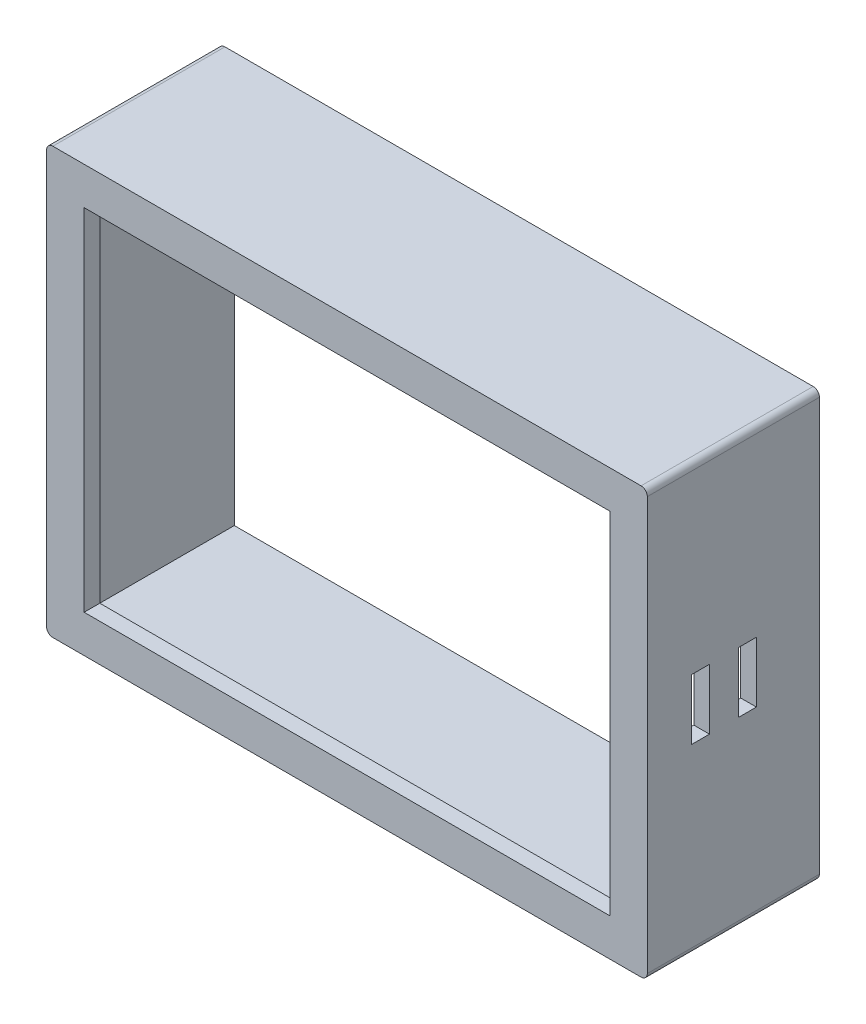
SolidWorks part; units mm, degrees
ref_plane "Front Plane" through (0, 0, 0) normal (0, 0, 1) x (1, 0, 0)
ref_plane "Top Plane" through (0, 0, 0) normal (0, 1, 0) x (1, 0, 0)
ref_plane "Right Plane" through (0, 0, 0) normal (1, 0, 0) x (0, 0, -1)
sketch "Sketch1" plane through (0, 0, 0) normal (0, 0, 1) x (1, 0, 0)
  line L0 (-48, 34) -> (48, 34)
  line L1 (-42, 28) -> (42, 28)
  line L2 (-42, 28) -> (-42, -28)
  line L3 (-42, -28) -> (42, -28)
  line L4 (42, 28) -> (42, -28)
  line L5 (-42, 28) -> (42, -28) construction
  line L6 (-42, -28) -> (42, 28) construction
  line L7 (48, 34) -> (48, -34)
  line L8 (-48, -34) -> (48, -34)
  line L9 (-48, 34) -> (-48, -34)
  point P0 (0, 0)
  dimension "D1" = 56
  dimension "D2" = 84
  dimension "D3" = 6
extrude "Boss-Extrude1" add sketch "Sketch1" against normal blind 2.5
sketch "Sketch2" plane through (0, 0, -2.5) normal (0, 0, -1) x (-1, 0, 0)
  line L4 (48, -34) -> (-48, -34) construction
  line L5 (48, 34) -> (48, -34) construction
  line L6 (-48, 34) -> (48, 34) construction
  line L7 (-48, -34) -> (-48, 34) construction
  line L8 (-45.5, -31.5) -> (45.5, -31.5)
  line L9 (45.5, -31.5) -> (45.5, 31.5)
  line L10 (45.5, 31.5) -> (-45.5, 31.5)
  line L11 (-45.5, 31.5) -> (-45.5, -31.5)
  line L12 (-45.5, -31.5) -> (45.5, -31.5)
  line L13 (45.5, -31.5) -> (45.5, 31.5)
  line L14 (45.5, 31.5) -> (-45.5, 31.5)
  line L15 (-45.5, 31.5) -> (-45.5, -31.5)
  line L16 (48, -34) -> (-48, -34)
  line L17 (48, 34) -> (48, -34)
  line L18 (-48, 34) -> (48, 34)
  line L19 (-48, -34) -> (-48, 34)
  dimension "D1" = 2.5
extrude "Boss-Extrude2" add sketch "Sketch2" along normal blind 25
fillet "Fillet1" radius 1 4 edges at (-48, -34, -13.75) (48, -34, -13.75) (48, 34, -13.75) (-48, 34, -13.75)
sketch "Sketch3" plane through (48, 0, 0) normal (1, 0, 0) x (0, 0, -1)
  line L0 (17.4299, 4.8349) -> (17.4299, -4.8349)
  line L1 (7.0648, 4.8349) -> (9.9299, 4.8349)
  line L2 (7.0648, 4.8349) -> (7.0648, -4.8349)
  line L3 (7.0648, -4.8349) -> (9.9299, -4.8349)
  line L4 (9.9299, 4.8349) -> (9.9299, -4.8349)
  line L5 (7.0648, 4.8349) -> (9.9299, -4.8349) construction
  line L6 (7.0648, -4.8349) -> (9.9299, 4.8349) construction
  line L7 (14.5648, -4.8349) -> (17.4299, -4.8349)
  line L8 (14.5648, 4.8349) -> (14.5648, -4.8349)
  line L9 (14.5648, 4.8349) -> (17.4299, 4.8349)
  point P0 (8.4973, 0)
  dimension "D1" = 2
extrude "Cut-Extrude1" cut sketch "Sketch3" against normal up to surface (2.5 mm away) up to face at (45.5, 0, -15)
